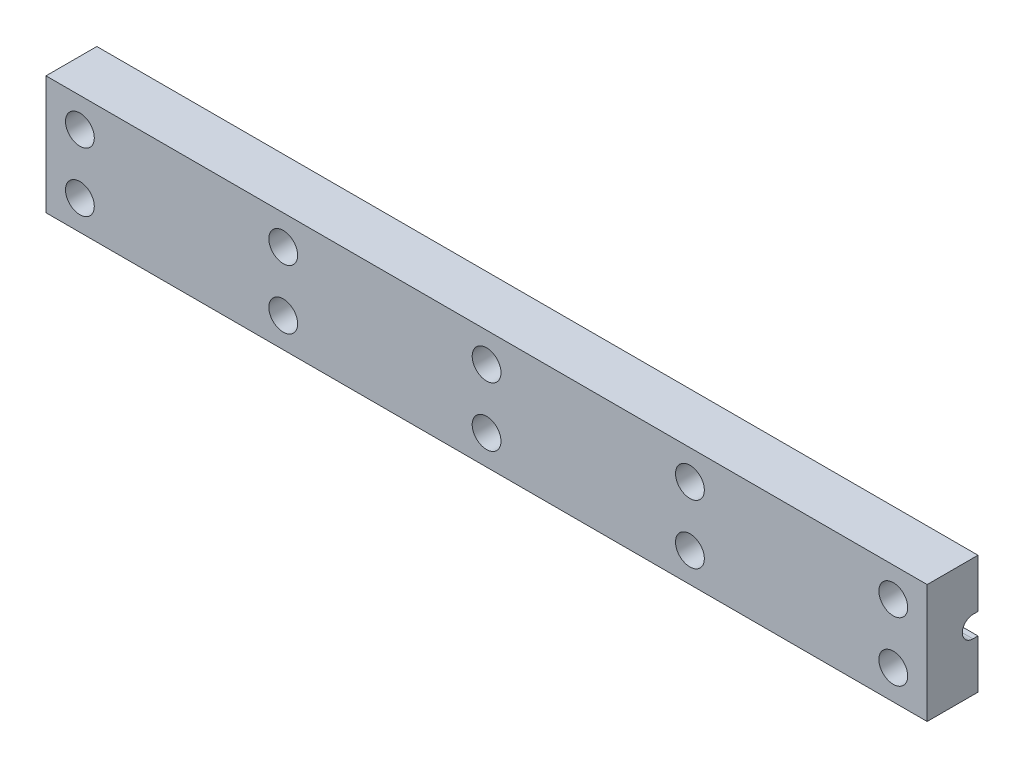
SolidWorks part; units mm, degrees
ref_plane "Front Plane" through (0, 0, 0) normal (0, 0, 1) x (1, 0, 0)
ref_plane "Top Plane" through (0, 0, 0) normal (0, 1, 0) x (1, 0, 0)
ref_plane "Right Plane" through (0, 0, 0) normal (1, 0, 0) x (0, 0, -1)
ref_plane "Plane1" through (190.6451, 0, 0) normal (1, 0, 0) x (0, 0, -1)
sketch "Sketch1" plane through (190.6451, 0, 0) normal (1, 0, 0) x (0, 0, -1)
  line L0 (-246.9709, 208.1635) -> (-246.9709, 205.1635) construction
  line L1 (-240.9709, 205.1635) -> (-240.9709, 208.1635) construction
  line L2 (-240.9709, 208.1635) -> (-246.9709, 208.1635) construction
  line L3 (-240.9709, 199.9135) -> (-241.5709, 199.9135) construction
  line L4 (-241.5709, 202.4135) -> (-240.9709, 202.4135) construction
  line L5 (-240.9709, 202.4135) -> (-240.9709, 205.1635) construction
  line L6 (-246.9709, 205.1635) -> (-246.9709, 197.1635) construction
  line L7 (-240.9709, 197.1635) -> (-240.9709, 199.9135) construction
  line L8 (-246.9709, 197.1635) -> (-246.9709, 194.1635) construction
  line L9 (-246.9709, 194.1635) -> (-240.9709, 194.1635) construction
  line L10 (-240.9709, 194.1635) -> (-240.9709, 197.1635) construction
  line L11 (-246.9709, 208.1635) -> (-246.9709, 205.1635)
  line L12 (-240.9709, 205.1635) -> (-240.9709, 208.1635)
  line L13 (-240.9709, 208.1635) -> (-246.9709, 208.1635)
  line L14 (-240.9709, 199.9135) -> (-241.5709, 199.9135)
  line L15 (-241.5709, 202.4135) -> (-240.9709, 202.4135)
  line L16 (-240.9709, 202.4135) -> (-240.9709, 205.1635)
  line L17 (-246.9709, 205.1635) -> (-246.9709, 197.1635)
  line L18 (-240.9709, 197.1635) -> (-240.9709, 199.9135)
  line L19 (-246.9709, 197.1635) -> (-246.9709, 194.1635)
  line L20 (-246.9709, 194.1635) -> (-240.9709, 194.1635)
  line L21 (-240.9709, 194.1635) -> (-240.9709, 197.1635)
  arc A0 (-241.5709, 202.4135) -> (-241.5709, 199.9135) centre (-241.5709, 201.1635) ccw construction
  arc A1 (-241.5709, 202.4135) -> (-241.5709, 199.9135) centre (-241.5709, 201.1635) ccw
extrude "Boss-Extrude1" add sketch "Sketch1" along normal blind 60 and the other way blind 20
sketch "Sketch2" plane through (0, 0, 246.9709) normal (0, 0, 1) x (1, 0, 0)
  line L0 (170.6451, 201.1635) -> (250.6451, 201.1635) construction
  line L1 (170.6451, 208.1635) -> (170.6451, 194.1635) construction
  line L2 (170.6451, 201.1635) -> (170.6451, 208.1635) construction
  line L3 (170.6451, 204.6635) -> (250.6451, 204.6635) construction
  line L4 (170.6451, 194.1635) -> (250.6451, 194.1635)
  line L5 (250.6451, 194.1635) -> (250.6451, 208.1635)
  line L6 (250.6451, 208.1635) -> (170.6451, 208.1635)
  line L7 (170.6451, 208.1635) -> (170.6451, 194.1635)
  line L8 (170.6451, 194.1635) -> (250.6451, 194.1635) construction
  line L9 (250.6451, 194.1635) -> (250.6451, 208.1635) construction
  line L10 (250.6451, 208.1635) -> (170.6451, 208.1635) construction
  line L12 (250.6451, 201.1635) -> (250.6451, 194.1635)
  line L13 (250.6451, 197.6635) -> (170.6451, 197.6635) construction
  line L15 (246.6451, 197.6635) -> (250.6451, 197.6635)
  line L16 (174.6451, 197.6635) -> (170.6451, 197.6635)
  line L17 (246.6451, 197.6635) -> (222.6451, 197.6635) construction
  line L18 (174.6451, 197.6635) -> (198.6451, 197.6635)
  line L20 (246.6451, 204.6635) -> (222.6451, 204.6635) construction
  circle A0 centre (246.6451, 197.6635) radius 1.7
  circle A2 centre (174.6451, 197.6635) radius 1.7
  circle A3 centre (198.6451, 197.6635) radius 1.7
  circle A4 centre (222.6451, 197.6635) radius 1.7
  circle A5 centre (174.6451, 204.6635) radius 1.7
  circle A6 centre (198.6451, 204.6635) radius 1.7
  circle A7 centre (222.6451, 204.6635) radius 1.7
  circle A8 centre (246.6451, 204.6635) radius 1.7
  dimension "D2" = 3.4
  dimension "D3" = 4
  dimension "D4" = 4
  dimension "D5" = 24
  dimension "D6" = 24
  dimension "D1" = 0
extrude "Cut-Extrude1" cut sketch "Sketch2" against normal blind 10
sketch "Sketch3" plane through (170.6451, 0, 0) normal (-1, 0, 0) x (0, 0, 1)
  line L7 (246.9709, 208.1635) -> (240.9709, 208.1635)
  line L8 (240.9709, 208.1635) -> (240.9709, 202.4135)
  line L9 (240.9709, 202.4135) -> (241.5709, 202.4135)
  line L10 (241.5709, 199.9135) -> (240.9709, 199.9135)
  line L11 (240.9709, 199.9135) -> (240.9709, 194.1635)
  line L12 (240.9709, 194.1635) -> (246.9709, 194.1635)
  line L13 (246.9709, 194.1635) -> (246.9709, 208.1635)
  line L14 (246.9709, 208.1635) -> (240.9709, 208.1635)
  line L15 (240.9709, 208.1635) -> (240.9709, 202.4135)
  line L16 (240.9709, 202.4135) -> (241.5709, 202.4135)
  line L17 (241.5709, 199.9135) -> (240.9709, 199.9135)
  line L18 (240.9709, 199.9135) -> (240.9709, 194.1635)
  line L19 (240.9709, 194.1635) -> (246.9709, 194.1635)
  line L22 (246.9709, 194.1635) -> (246.9709, 208.1635)
  arc A1 (241.5709, 199.9135) -> (241.5709, 202.4135) centre (241.5709, 201.1635) ccw
  arc A2 (241.5709, 199.9135) -> (241.5709, 202.4135) centre (241.5709, 201.1635) ccw
  dimension "D1" = 0
extrude "Boss-Extrude2" add sketch "Sketch3" along normal blind 24
sketch "Sketch4" plane through (0, 0, 246.9709) normal (0, 0, 1) x (1, 0, 0)
  line L0 (174.6451, 197.6635) -> (150.6451, 197.6635) construction
  circle A4 centre (150.6451, 197.6635) radius 1.7
  circle A5 centre (150.6451, 204.6635) radius 1.7
extrude "Cut-Extrude2" cut sketch "Sketch4" against normal blind 24
equation "\"D6@Sketch2\"=\"D5@Sketch2\""
